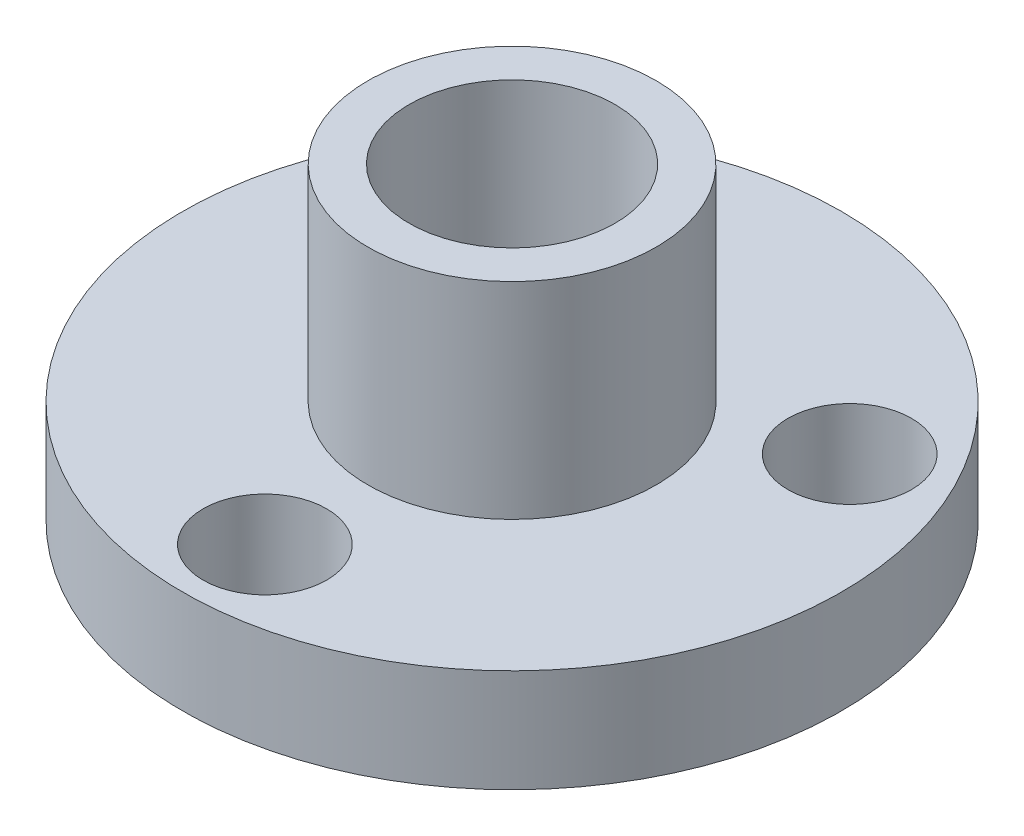
SolidWorks part; units mm, degrees
ref_plane "Plan de face" through (0, 0, 0) normal (0, 0, 1) x (1, 0, 0)
ref_plane "Plan de dessus" through (0, 0, 0) normal (0, 1, 0) x (1, 0, 0)
ref_plane "Plan de droite" through (0, 0, 0) normal (1, 0, 0) x (0, 0, -1)
sketch "Esquisse1" plane through (0, 0, 0) normal (0, 0, 1) x (1, 0, 0)
  line L0 (0, 0) -> (0, 7.6852) construction
  line L1 (2.5, 0) -> (8, 0)
  line L2 (8, 0) -> (8, 2.5)
  line L3 (8, 2.5) -> (3.5, 2.5)
  line L4 (3.5, 2.5) -> (3.5, 7.5)
  line L5 (3.5, 7.5) -> (2.5, 7.5)
  line L6 (2.5, 7.5) -> (2.5, 0)
  point P9 (5.3575, 1.3987)
  dimension "D1" = 5
  dimension "D2" = 7
  dimension "D3" = 5
  dimension "D4" = 2.5
  dimension "D5" = 16
revolve "Révolution1" add sketch "Esquisse1" angle 360 about L0
sketch "Esquisse2" plane through (0, 0, 0) normal (0, -1, 0) x (1, 0, 0)
  line L0 (0, 6) -> (5.1962, -3) construction
  line L1 (5.1962, -3) -> (-5.1962, -3) construction
  line L2 (-5.1962, -3) -> (0, 6) construction
  circle A0 centre (0, 0) radius 6 construction
  circle A1 centre (0, 6) radius 1.5
  circle A2 centre (5.1962, -3) radius 1.5
  circle A3 centre (-5.1962, -3) radius 1.5
  dimension "D1" = 3
  dimension "D2" = 12
extrude "Enlèv. mat.-Extru.1" cut sketch "Esquisse2" against normal through all
